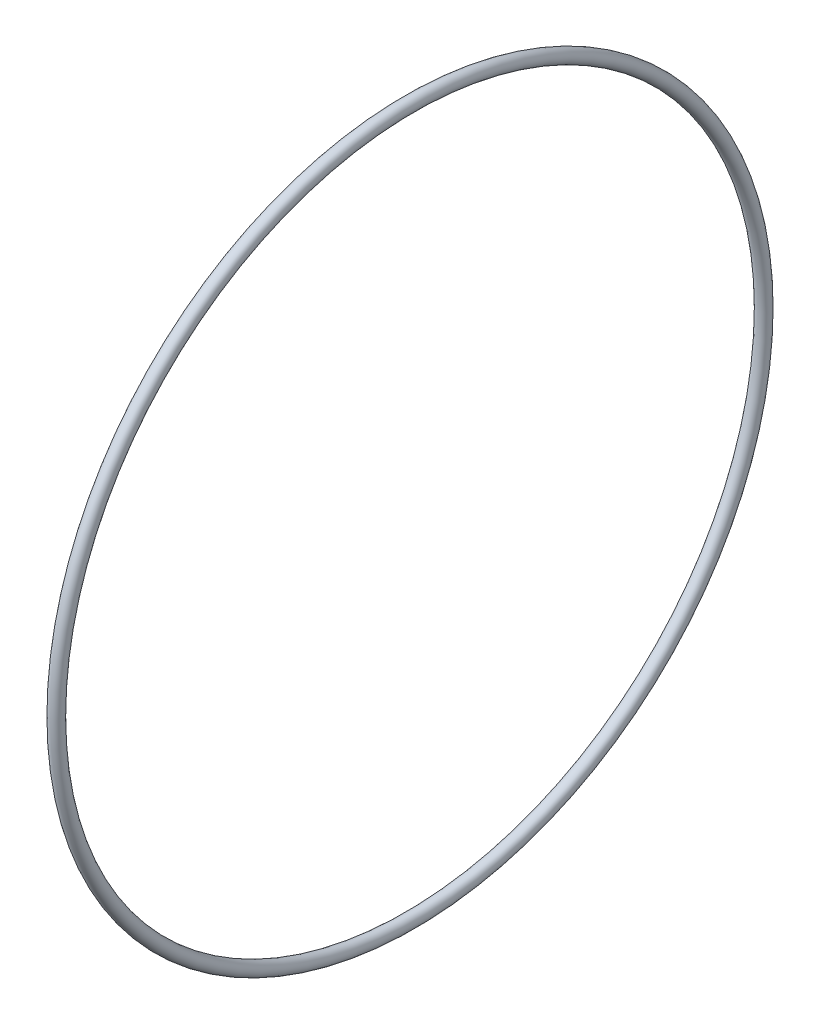
SolidWorks part; units mm, degrees
ref_plane "Front Plane" through (0, 0, 0) normal (0, 0, 1) x (1, 0, 0)
ref_plane "Top Plane" through (0, 0, 0) normal (0, 1, 0) x (1, 0, 0)
ref_plane "Right Plane" through (0, 0, 0) normal (1, 0, 0) x (0, 0, -1)
sketch "Sketch1" plane through (0, 0, 0) normal (1, 0, 0) x (0, 0, -1)
  circle A0 centre (0, 0) radius 139.3825
  dimension "D1" = 278.765
sketch "Sketch3" plane through (0, 0, 0) normal (0, 0, 1) x (1, 0, 0)
  line L0 (0, -139.3825) -> (0, 139.3825) construction
  line L1 (0, 142.0495) -> (0, 139.3825) construction
  circle A0 centre (0, 142.0495) radius 2.667
  dimension "D1" = 5.334
sweep "Sweep1" add profiles "Sketch3" path "Sketch1"
